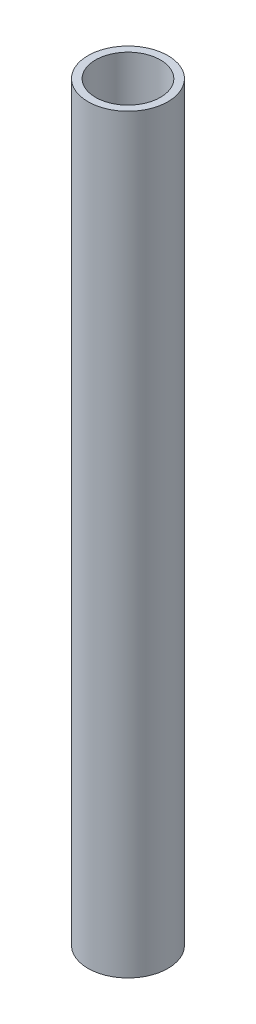
SolidWorks part; units mm, degrees
material "СТ3КП"
ref_plane "Спереди" through (0, 0, 0) normal (0, 0, 1) x (1, 0, 0)
ref_plane "Сверху" through (0, 0, 0) normal (0, 1, 0) x (1, 0, 0)
ref_plane "Справа" through (0, 0, 0) normal (1, 0, 0) x (0, 0, -1)
sketch "Эскиз1" plane through (0, 0, 0) normal (0, 1, 0) x (1, 0, 0)
  line L0 (0, 200889.2922) -> (0, -249032.8193) construction
  line L1 (-170, 9.15) -> (170, 9.15) construction
  circle B0 centre (0, -1.5) radius 8.65
  circle B1 centre (0, -1.5) radius 10.65
sketch_block_instance "Труба 21_3х2 1_2-1"
sketch_block "Труба 21_3х2 1_2" parameters "D2"=21.3, "D1"=2
extrude "Бобышка-Вытянуть1" add sketch "Эскиз1" along normal up to vertex (200 mm away)
